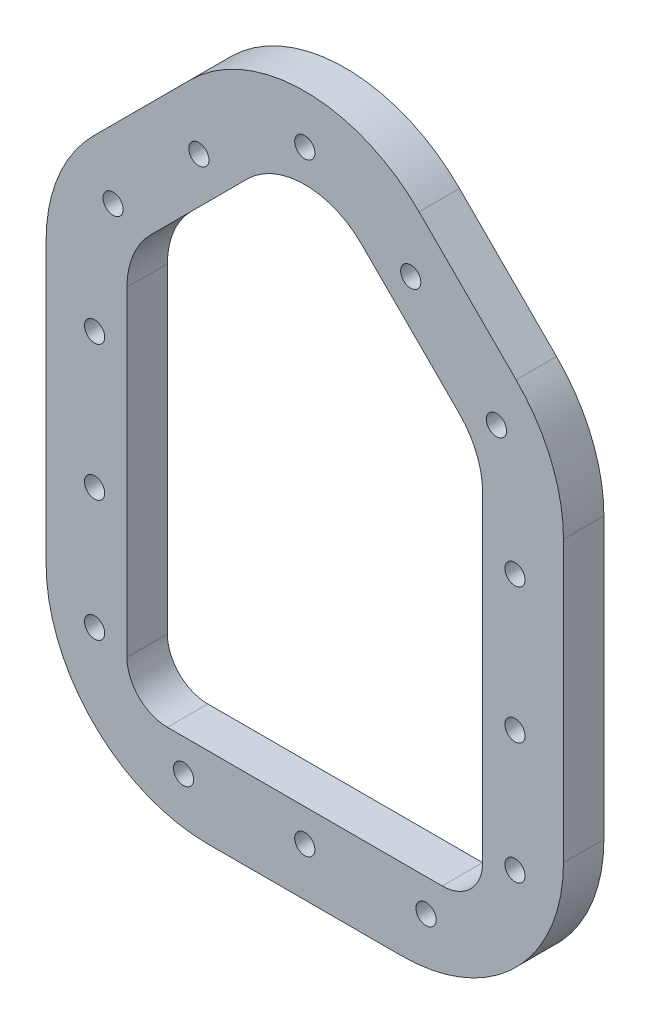
SolidWorks part; units mm, degrees
ref_plane "Front Plane" through (0, 0, 0) normal (0, 0, 1) x (1, 0, 0)
ref_plane "Top Plane" through (0, 0, 0) normal (0, 1, 0) x (1, 0, 0)
ref_plane "Right Plane" through (0, 0, 0) normal (1, 0, 0) x (0, 0, -1)
sketch "Sketch1" plane through (0, 0, 0) normal (0, 0, 1) x (1, 0, 0)
  line L0 (0, 107) -> (0, 0) construction
  line L1 (0, 107) -> (-37, 70) construction
  line L2 (-37, 70) -> (-37, 0) construction
  line L3 (-37, 0) -> (37, 0) construction
  line L4 (37, 70) -> (37, 0) construction
  line L5 (0, 107) -> (37, 70) construction
  line L6 (32, 5) -> (-32, 5)
  line L7 (-32, 5) -> (-32, 59.6447)
  line L8 (-26.1421, 73.7868) -> (-14.1421, 85.7868)
  line L9 (32, 5) -> (32, 59.6447)
  line L10 (26.1421, 73.7868) -> (14.1421, 85.7868)
  line L11 (0, 85.6447) -> (-5.799, 85.6447) construction
  line L12 (-5.799, 85.6447) -> (-26, 65.4437) construction
  line L13 (-26, 65.4437) -> (-26, 11) construction
  line L14 (-26, 11) -> (0, 11) construction
  line L15 (-22, 59.6447) -> (-22, 15)
  line L16 (-22, 15) -> (22, 15)
  line L17 (-19.0711, 66.7157) -> (-7.0711, 78.7157)
  line L18 (22, 59.6447) -> (22, 15)
  line L19 (19.0711, 66.7157) -> (7.0711, 78.7157)
  arc A0 (14.1421, 85.7868) -> (-14.1421, 85.7868) centre (0, 71.6447) ccw
  arc A1 (-26.1421, 73.7868) -> (-32, 59.6447) centre (-12, 59.6447) ccw
  arc A2 (32, 59.6447) -> (26.1421, 73.7868) centre (12, 59.6447) ccw
  circle A3 centre (0, 85.6447) radius 1.25
  circle A4 centre (-13.1021, 78.3416) radius 1.25
  circle A5 centre (-23.7087, 67.735) radius 1.25
  circle A6 centre (-26, 52.911) radius 1.25
  circle A7 centre (-26, 36.198) radius 1.25
  circle A8 centre (-26, 21.198) radius 1.25
  circle A9 centre (0, 11) radius 1.25
  circle A10 centre (-15, 11) radius 1.25
  arc A11 (-32, 20) -> (-17, 5) centre (-17, 20) ccw construction
  circle A12 centre (13.1021, 78.3416) radius 1.25
  circle A13 centre (23.7087, 67.735) radius 1.25
  circle A14 centre (26, 52.911) radius 1.25
  circle A15 centre (26, 36.198) radius 1.25
  circle A16 centre (26, 21.198) radius 1.25
  circle A17 centre (15, 11) radius 1.25
  arc A18 (22, 59.6447) -> (19.0711, 66.7157) centre (12, 59.6447) ccw
  arc A19 (-19.0711, 66.7157) -> (-22, 59.6447) centre (-12, 59.6447) ccw
  arc A20 (7.0711, 78.7157) -> (-7.0711, 78.7157) centre (0, 71.6447) ccw
  point P13 (0, 5)
  point P16 (0, 99.9289)
  point P19 (-32, 67.9289)
  point P22 (32, 67.9289)
  point P49 (0, 15)
  point P64 (22, 63.7868)
  point P67 (-22, 63.7868)
  point P70 (0, 85.7868)
  dimension "D7" = 20
  dimension "D8" = 20
  dimension "D9" = 20
  dimension "D10" = 6
  dimension "D14" = 2.5
  dimension "D15" = 15
  dimension "D25" = 10
  dimension "D26" = 10
  dimension "D27" = 10
  dimension "D1" = 45
  dimension "D2" = 37
  dimension "D3" = 70
  dimension "D4" = 5
  dimension "D5" = 5
  dimension "D6" = 5
  dimension "D11" = 14
  dimension "D12" = 6
  dimension "D13" = 6
  dimension "D16" = 15
  dimension "D17" = 15
  dimension "D18" = 15
  dimension "D19" = 15
  dimension "D20" = 15
  dimension "D21" = 15
  dimension "D22" = 4
  dimension "D23" = 4
  dimension "D24" = 4
extrude "Boss-Extrude1" add sketch "Sketch1" along normal blind 5
fillet "Fillet1" radius 20 2 edges at (32, 5, 2.5) (-32, 5, 2.5)
fillet "Fillet2" radius 5 2 edges at (22, 15, 2.5) (-22, 15, 2.5)
